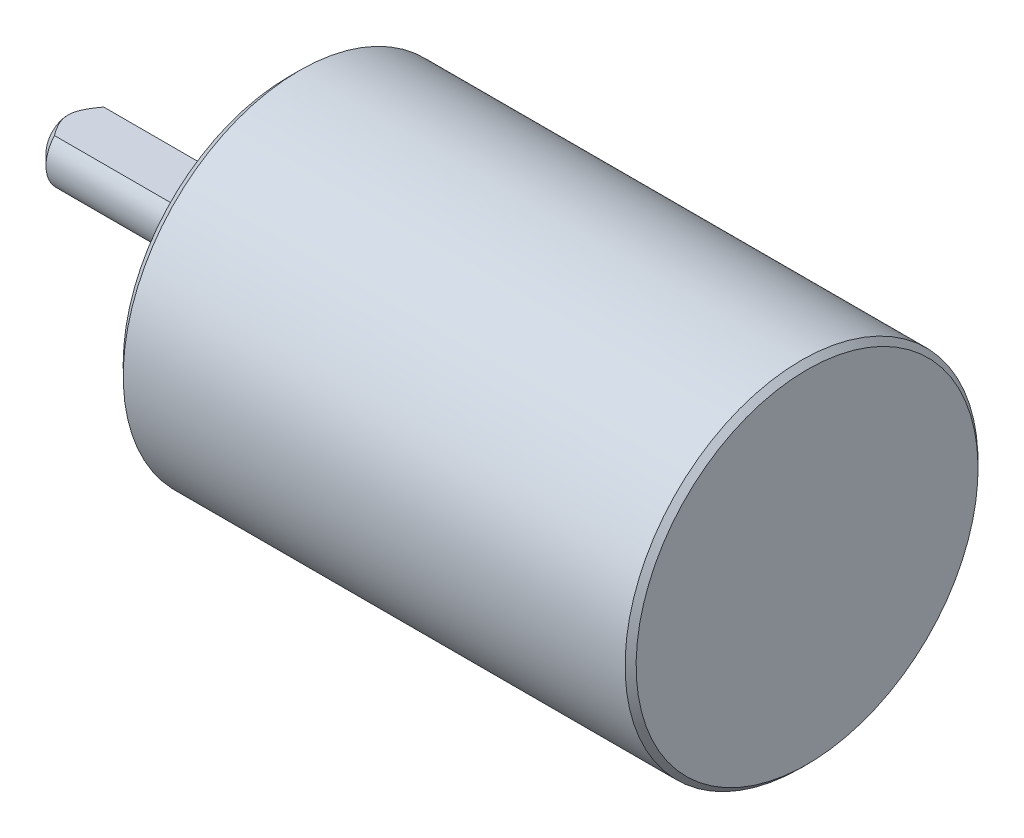
SolidWorks part; units mm, degrees
ref_plane "Plan de face" through (0, 0, 0) normal (0, 0, 1) x (1, 0, 0)
ref_plane "Plan de dessus" through (0, 0, 0) normal (0, 1, 0) x (1, 0, 0)
ref_plane "Plan de droite" through (0, 0, 0) normal (1, 0, 0) x (0, 0, -1)
sketch "Esquisse1" plane through (0, 0, 0) normal (0, 0, 1) x (1, 0, 0)
  line L0 (0, 0) -> (0, 3)
  line L1 (0, 3) -> (17, 3)
  line L2 (17, 3) -> (17, 10)
  line L3 (17, 10) -> (20, 10)
  line L4 (20, 10) -> (20, 16)
  line L5 (20, 16) -> (67, 16)
  line L6 (67, 16) -> (67, 0)
  line L7 (67, 0) -> (0, 0)
  dimension "D1" = 3
  dimension "D2" = 10
  dimension "D3" = 16
  dimension "D4" = 47
  dimension "D5" = 3
  dimension "D6" = 20
revolve "Révolution1" add sketch "Esquisse1" angle 360 about L7
hole_wizard "Trou taraudé M3x0.51" positions "Esquisse3" profile "Esquisse2" tap size "M3x0.5" standard "Ansi Metric"
sketch "Esquisse3" plane through (20, 0, 0) normal (-1, 0, 0) x (0, 0, 1)
  circle A0 centre (0, 0) radius 13
  point P5 (-13, 0)
  point P7 (0, 13)
  point P9 (13, 0)
  point P11 (0, -13)
  dimension "D1" = 26
sketch "Esquisse2" plane through (20, 0, -13) normal (0, 1, 0) x (0, 0, 1)
  line L0 (0, 0) -> (0, 4.7511)
  line L1 (0, 4.7511) -> (1.25, 4)
  line L2 (1.25, 4) -> (1.25, 0)
  line L5 (1.25, 0) -> (0, 0)
  line L10 (0, 4.7511) -> (-1.25, 4) construction
  line L11 (0, -6.35) -> (0, 107.95) construction
  dimension "Diamètre du trou pour taraudage" = 2.5
  dimension "Profondeur du trou pour taraudage" = 4
  dimension "Angle de pointe" = 118
cosmetic thread "Filetage de perçage1"
cosmetic thread "Filetage de perçage2"
cosmetic thread "Filetage de perçage3"
cosmetic thread "Filetage de perçage4"
chamfer "Chanfrein1" distance 0.5 angle 45 1 edges at (67, 16, 0)
chamfer "Chanfrein2" distance 1 angle 45 1 edges at (20, 16, 0)
fillet "Congé1" radius 1 1 edges at (17, 10, 0)
chamfer "Chanfrein3" distance 1 angle 45 1 edges at (0, 3, 0)
ref_plane "Plan1" through (0, 3, 0) normal (0, 1, 0) x (1, 0, 0)
sketch "Esquisse4" plane through (0, 3, 0) normal (0, 1, 0) x (1, 0, 0)
  line L1 (15, 3) -> (0, 3)
  line L2 (15, 3) -> (15, -3)
  line L3 (15, -3) -> (0, -3)
  line L4 (0, 3) -> (0, -3)
  line L5 (15, 3) -> (0, -3) construction
  line L6 (15, -3) -> (0, 3) construction
  point P0 (7.5, 0)
  point P5 (0, 0)
  dimension "D1" = 15
extrude "Enlèv. mat.-Extru.1" cut sketch "Esquisse4" against normal blind 1
